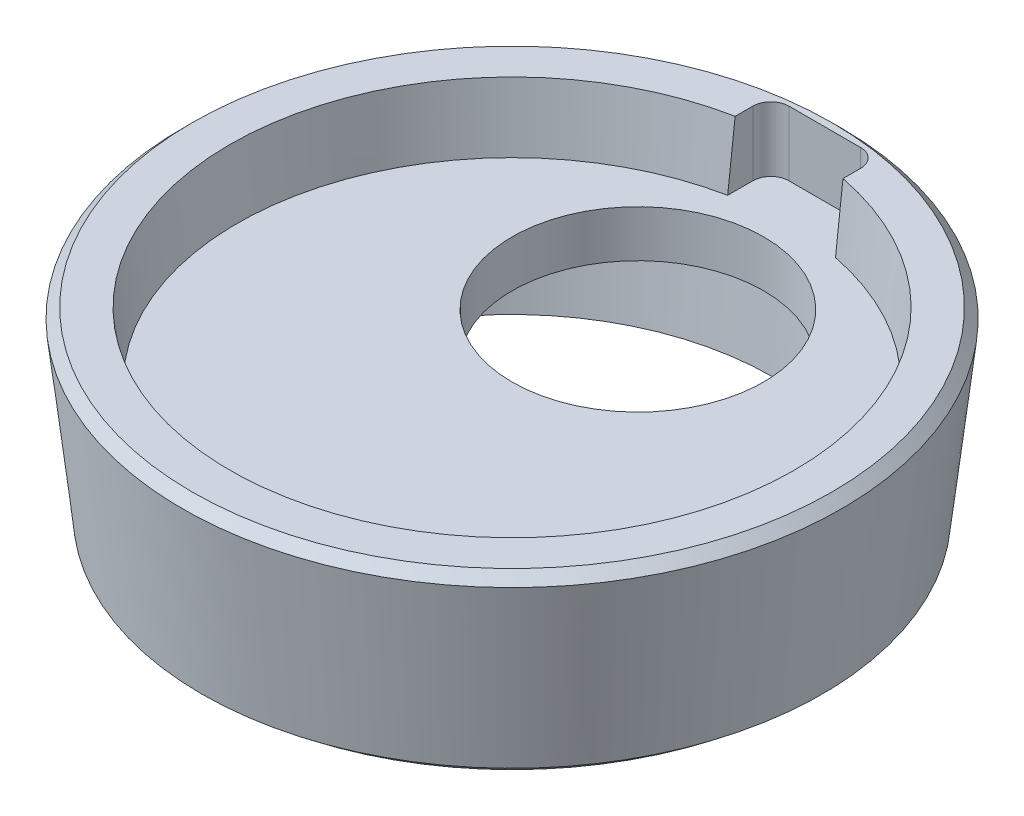
SolidWorks part; units mm, degrees
ref_plane "Front Plane" through (0, 0, 0) normal (0, 0, 1) x (1, 0, 0)
ref_plane "Top Plane" through (0, 0, 0) normal (0, 1, 0) x (1, 0, 0)
ref_plane "Right Plane" through (0, 0, 0) normal (1, 0, 0) x (0, 0, -1)
sketch "Sketch1" plane through (0, 0, 0) normal (0, 0, 1) x (1, 0, 0)
  line L0 (0, 0) -> (0, -15.8583) construction
  line L1 (0, 0) -> (-17.2, 0)
  line L2 (-17.2, 0) -> (-15.1, -12)
  line L3 (-15.1, -12) -> (0, -12)
  line L4 (0, 0) -> (0, -12)
  dimension "D1" = 34.4
  dimension "D2" = 30.2
  dimension "D3" = 12
revolve "Revolve1" add sketch "Sketch1" angle 360 about L0
sketch "Sketch2" plane through (0, 0, 0) normal (0, 1, 0) x (1, 0, 0)
  line L0 (0, 0) -> (0, -13.7261) construction
  line L1 (-9.1, -5.8) -> (-7.3, -5.8)
  line L2 (-9.1, -5.8) -> (-9.1, -4)
  line L3 (-9.1, -4) -> (-7.3, -4)
  line L4 (9.1, -5.8) -> (9.1, -4)
  line L5 (-7.3, -5.8) -> (-7.3, -10.7569)
  line L6 (-7.3, -4) -> (-7.3, 0)
  line L7 (-7.3, 0) -> (-13, 0)
  line L8 (7.3, 0) -> (13, 0)
  line L9 (7.3, -4) -> (7.3, 0)
  line L10 (7.3, -5.8) -> (7.3, -10.7569)
  line L11 (7.3, -5.8) -> (9.1, -5.8)
  line L12 (7.3, -4) -> (9.1, -4)
  arc A0 (13, 0) -> (-13, 0) centre (0, 0) ccw
  arc A1 (-7.3, -10.7569) -> (7.3, -10.7569) centre (0, 0) ccw
  dimension "D5" = 26
  dimension "D1" = 4
  dimension "D2" = 18.2
  dimension "D3" = 1.8
  dimension "D4" = 18.2
  dimension "D6" = 1.8
extrude "Cut-Extrude1" cut sketch "Sketch2" against normal through all
sketch "Sketch3" plane through (0, 0, 0) normal (0, 1, 0) x (1, 0, 0)
  line L1 (-7.3, -4) -> (-9.1, -4) construction
  line L2 (-7.3, 0) -> (-7.3, -4) construction
  line L3 (0, 0) -> (0, -9.4106) construction
  circle A0 centre (-8.1, -4.9) radius 2
  circle A1 centre (8.1, -4.9) radius 2
  dimension "D1" = 4
  dimension "D2" = 0.9
  dimension "D3" = 0.8
extrude "Cut-Extrude2" cut sketch "Sketch3" against normal blind 2
sketch "Sketch6" plane through (0, 0, 0) normal (1, 0, 0) x (0, 0, -1)
  line L0 (0, 4.4) -> (0, 18.4608) construction
  line L1 (17.2, 0) -> (18.4, 10.6)
  line L2 (18.4, 10.6) -> (15.7019, 10.6)
  line L3 (0, 4.4) -> (0, 7)
  line L4 (14.5019, 0) -> (17.2, 0)
  line L5 (14.5019, 0) -> (15, 4.4)
  line L6 (15, 4.4) -> (0, 4.4)
  line L7 (15.2943, 7) -> (15.7019, 10.6)
  line L8 (15.2943, 7) -> (0, 7)
  dimension "D1" = 36.8
  dimension "D2" = 10.6
  dimension "D3" = 30
  dimension "D4" = 4.4
  dimension "D5" = 2.6
  dimension "D6" = 31.4038
revolve "Revolve2" add sketch "Sketch6" angle 360 about L0
sketch "Sketch8" plane through (0, -12, 0) normal (0, -1, 0) x (1, 0, 0)
  circle A0 centre (0, 0) radius 25.2248
extrude "Cut-Extrude4" cut sketch "Sketch8" against normal blind 12
sketch "Sketch11" plane through (0, 7, 0) normal (0, 1, 0) x (1, 0, 0)
  line L0 (0, 0) -> (0, 7) construction
  circle A0 centre (0, 7) radius 7
  dimension "D1" = 14
extrude "Cut-Extrude6" cut sketch "Sketch11" against normal through all
sketch "Sketch12" plane through (0, 10.6, 0) normal (0, 1, 0) x (1, 0, 0)
  line L0 (3, 16.4) -> (3, 14.7885)
  line L1 (0, 0) -> (0, 20.1204) construction
  line L2 (2, 17.4) -> (-2, 17.4)
  line L3 (-3, 16.4) -> (-3, 14.7885)
  line L4 (-3, 14.7885) -> (3, 14.7885)
  arc A2 (3, 16.4) -> (2, 17.4) centre (2, 16.4) ccw
  arc A3 (-3, 16.4) -> (-2, 17.4) centre (-2, 16.4) cw
  point P11 (0, 17.4)
  point P12 (3, 17.4)
  point P15 (-3, 17.4)
  dimension "D3" = 1
  dimension "D1" = 6
  dimension "D2" = 17.4
extrude "Cut-Extrude7" cut sketch "Sketch12" against normal up to surface (3.6 mm away) up to face at (0, 7, 0)
chamfer "Chamfer1" distance 0.6 angle 45 2 edges at (0, 0, -17.2) (0, 10.6, -18.4)
